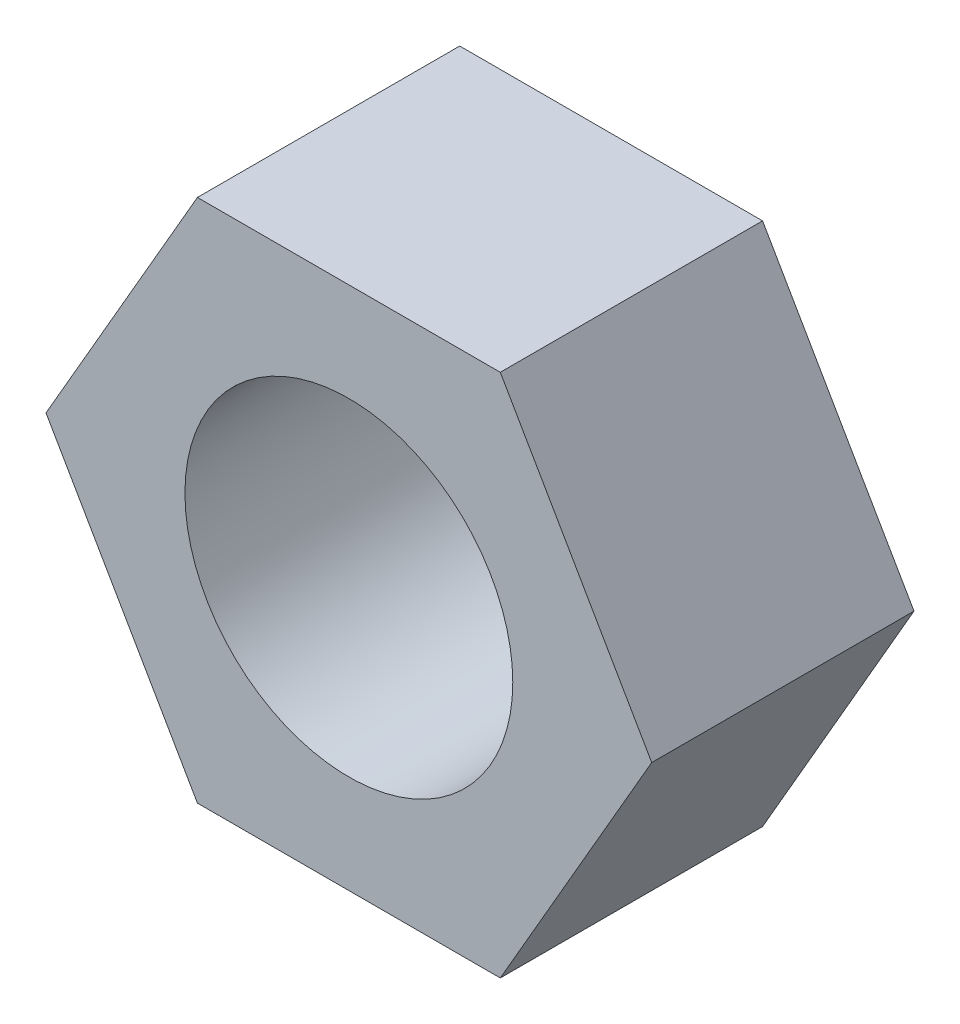
SolidWorks part; units mm, degrees
ref_plane "Alzado" through (0, 0, 0) normal (0, 0, 1) x (1, 0, 0)
ref_plane "Planta" through (0, 0, 0) normal (0, 1, 0) x (1, 0, 0)
ref_plane "Vista lateral" through (0, 0, 0) normal (1, 0, 0) x (0, 0, -1)
sketch "Croquis1" plane through (0, 0, 0) normal (0, 0, 1) x (1, 0, 0)
  line L1 (4.6188, 0) -> (2.3094, 4)
  line L2 (2.3094, 4) -> (-2.3094, 4)
  line L3 (-2.3094, 4) -> (-4.6188, 0)
  line L4 (-4.6188, 0) -> (-2.3094, -4)
  line L5 (-2.3094, -4) -> (2.3094, -4)
  line L6 (2.3094, -4) -> (4.6188, 0)
  circle A0 centre (0, 0) radius 2.5
  circle A1 centre (0, 0) radius 4 construction
  dimension "D2" = 5
  dimension "D1" = 8
extrude "Saliente-Extruir1" add sketch "Croquis1" along normal blind 4
